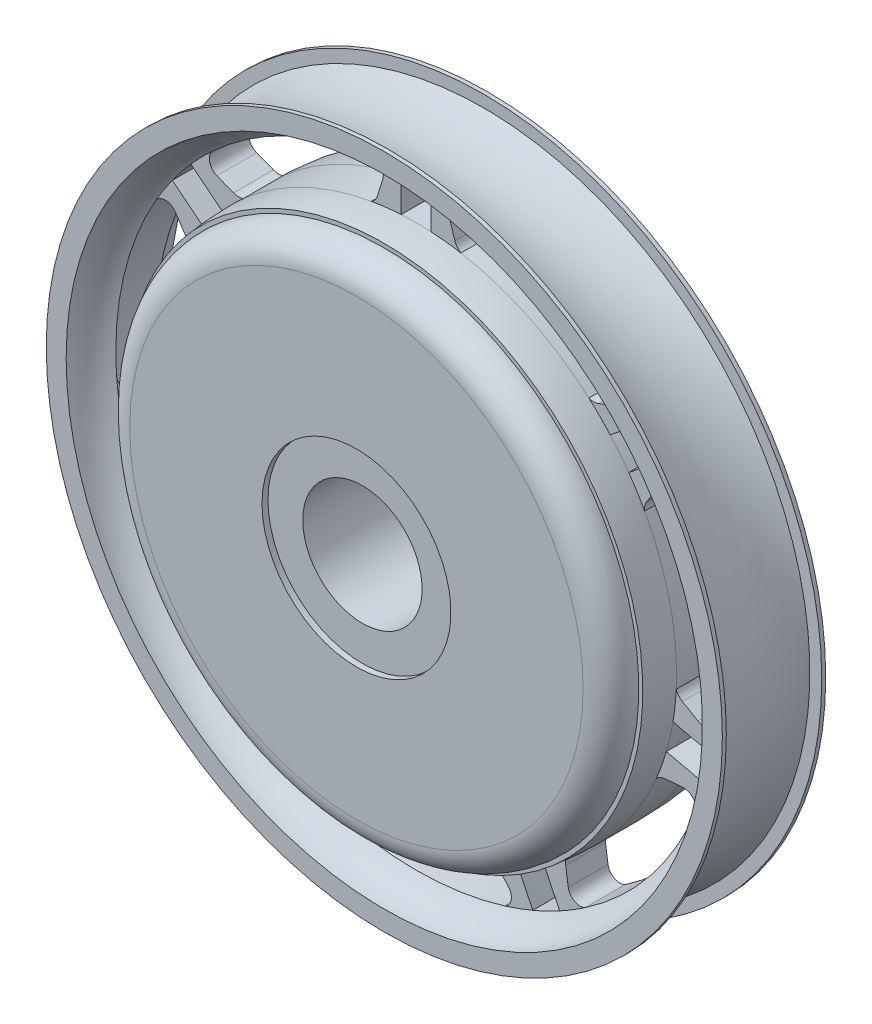
SolidWorks part; units mm, degrees
ref_plane "Спереди" through (0, 0, 0) normal (0, 0, 1) x (1, 0, 0)
ref_plane "Сверху" through (0, 0, 0) normal (0, 1, 0) x (1, 0, 0)
ref_plane "Справа" through (0, 0, 0) normal (1, 0, 0) x (0, 0, -1)
other "Configuration Table"
sketch "Sketch2" plane through (0, 0, 0) normal (0, 1, 0) x (1, 0, 0)
  line L0 (-47.5, -40) -> (-114, -40)
  line L1 (-114, 40) -> (-47.5, 40)
  line L2 (-30, 37) -> (-30, -37)
  line L3 (0, 135.3674) -> (0, -254.0086) construction
  line L4 (-170, 121.9099) -> (-170, -139.6695) construction
  line L5 (-130, 26) -> (-128, 26)
  line L7 (-170, -24) -> (-170, -26)
  line L9 (-221.397, 0) -> (79.0762, 0) construction
  line L10 (-47.5, 40) -> (-47.5, 37)
  line L11 (-47.5, 37) -> (-30, 37)
  line L12 (-47.5, -40) -> (-47.5, -37)
  line L13 (-47.5, -37) -> (-30, -37)
  line L14 (-131, 10) -> (-151, 10)
  line L15 (-160, 26) -> (-170, 26)
  line L16 (-170, 26) -> (-170, 24)
  line L17 (-130, -26) -> (-128, -26)
  line L18 (-131, -10) -> (-151, -10)
  line L19 (-160, -26) -> (-170, -26)
  line L20 (-170, 24) -> (-164, 24)
  line L22 (-164, -24) -> (-170, -24)
  arc A2 (-114, 40) -> (-128, 26) centre (-114, 26) ccw
  arc A4 (-114, -40) -> (-128, -26) centre (-114, -26) cw
  arc A5 (-131, 10) -> (-130, 26) centre (-2.5, 10) cw
  arc A6 (-151, 10) -> (-160, 26) centre (-140.0127, 26.7116) cw
  arc A8 (-131, -10) -> (-130, -26) centre (-2.5, -10) ccw
  arc A9 (-151, -10) -> (-160, -26) centre (-140.0127, -26.7116) ccw
  arc A10 (-164, -24) -> (-164, 24) centre (-218.9909, 0) ccw
  dimension "D1" = 140
  dimension "D7" = 3
  dimension "D13" = 60
  dimension "D15" = 20
  dimension "D2" = 80
  dimension "D3" = 60
  dimension "D4" = 2
  dimension "D5" = 6
  dimension "D6" = 95
  dimension "D8" = 98
  dimension "D9" = 3
  dimension "D10" = 2
  dimension "D11" = 20
  dimension "D12" = 10
  dimension "D14" = 20
  dimension "D16" = 52
revolve "Revolve1" add sketch "Sketch2" angle 360 about L3
sketch "Sketch3" plane through (0, 0, 10) normal (0, 0, 1) x (1, 0, 0)
  line L0 (0, 11.3109) -> (0, 206.172) construction
  line L1 (-7.5, 150.8136) -> (-7.5, 130.7851)
  line L2 (7.5, 150.8136) -> (7.5, 130.7851)
  line L3 (-16.7754, 141.5175) -> (-19.4706, 132.9305)
  line L4 (-22.5, 187.0326) -> (-22.5, 75.6795) construction
  line L5 (16.7754, 141.5175) -> (19.4706, 132.9305)
  line L6 (113.2347, 99.8945) -> (97.5758, 87.4069)
  line L7 (122.587, 88.167) -> (106.9281, 75.6795)
  line L8 (100.1835, 101.3502) -> (91.7896, 98.1035)
  line L9 (121.1021, 75.1192) -> (116.0689, 67.6581)
  line L10 (148.7013, -26.2472) -> (129.175, -21.7905)
  line L11 (145.3635, -40.8711) -> (125.8372, -36.4144)
  line L12 (141.7022, -15.1358) -> (133.9303, -10.5974)
  line L13 (134.2365, -47.8454) -> (125.2651, -48.5622)
  line L14 (72.1928, -132.6243) -> (63.5028, -114.5792)
  line L15 (58.6783, -139.1325) -> (49.9883, -121.0875)
  line L16 (76.5162, -120.2243) -> (75.2188, -111.3183)
  line L17 (46.2881, -134.7814) -> (40.134, -128.2142)
  line L18 (-58.6783, -139.1325) -> (-49.9883, -121.0875)
  line L19 (-72.1928, -132.6243) -> (-63.5028, -114.5792)
  line L20 (-46.2881, -134.7814) -> (-40.134, -128.2142)
  line L21 (-76.5162, -120.2243) -> (-75.2188, -111.3183)
  line L22 (-145.3635, -40.8711) -> (-125.8372, -36.4144)
  line L23 (-148.7013, -26.2472) -> (-129.175, -21.7905)
  line L24 (-134.2365, -47.8454) -> (-125.2651, -48.5622)
  line L25 (-141.7022, -15.1358) -> (-133.9303, -10.5974)
  line L26 (-122.587, 88.167) -> (-106.9281, 75.6795)
  line L27 (-113.2347, 99.8945) -> (-97.5758, 87.4069)
  line L28 (-121.1021, 75.1192) -> (-116.0689, 67.6581)
  line L29 (-100.1835, 101.3502) -> (-91.7896, 98.1035)
  circle A0 centre (0, 0) radius 151 construction
  circle A1 centre (0, 0) radius 131 construction
  arc A2 (-19.4706, 132.9305) -> (-22.5, 129.0533) centre (-26.1493, 135.0268) cw
  arc A3 (-16.7754, 141.5175) -> (-22.5, 149.3143) centre (-22.5, 143.3143) ccw
  arc A4 (19.4706, 132.9305) -> (22.5, 129.0533) centre (26.1493, 135.0268) ccw
  circle A5 centre (0, 0) radius 151
  circle A6 centre (0, 0) radius 151
  arc A7 (16.7754, 141.5175) -> (22.5, 149.3143) centre (22.5, 143.3143) cw
  arc A8 (91.7896, 98.1035) -> (86.8694, 98.0546) centre (89.2644, 104.6322) cw
  arc A9 (100.1835, 101.3502) -> (102.7101, 110.6871) centre (98.0191, 106.9462) ccw
  arc A10 (116.0689, 67.6581) -> (114.9264, 62.8722) centre (121.872, 63.7435) ccw
  arc A11 (121.1021, 75.1192) -> (130.7671, 75.5047) centre (126.0761, 71.7638) cw
  arc A12 (133.9303, -10.5974) -> (130.8244, -6.7812) centre (137.4601, -4.5526) cw
  arc A13 (141.7022, -15.1358) -> (150.5774, -11.2897) centre (144.7278, -9.9545) ccw
  arc A14 (125.2651, -48.5622) -> (120.8109, -50.6529) centre (125.8226, -55.54) ccw
  arc A15 (134.2365, -47.8454) -> (140.5639, -55.1614) centre (134.7144, -53.8263) cw
  arc A16 (75.2188, -111.3183) -> (76.2659, -106.5106) centre (82.1456, -110.3092) cw
  arc A17 (76.5162, -120.2243) -> (85.0568, -124.7651) centre (82.4535, -119.3593) ccw
  arc A18 (40.134, -128.2142) -> (35.7223, -126.0354) centre (35.0262, -133.0007) ccw
  arc A19 (46.2881, -134.7814) -> (44.5132, -144.2899) centre (41.9099, -138.8841) cw
  arc A20 (-40.134, -128.2142) -> (-35.7223, -126.0354) centre (-35.0262, -133.0007) cw
  arc A21 (-46.2881, -134.7814) -> (-44.5132, -144.2899) centre (-41.9099, -138.8841) ccw
  arc A22 (-75.2188, -111.3183) -> (-76.2659, -106.5106) centre (-82.1456, -110.3092) ccw
  arc A23 (-76.5162, -120.2243) -> (-85.0568, -124.7651) centre (-82.4535, -119.3593) cw
  arc A24 (-125.2651, -48.5622) -> (-120.8109, -50.6529) centre (-125.8226, -55.54) cw
  arc A25 (-134.2365, -47.8454) -> (-140.5639, -55.1614) centre (-134.7144, -53.8263) ccw
  arc A26 (-133.9303, -10.5974) -> (-130.8244, -6.7812) centre (-137.4601, -4.5526) ccw
  arc A27 (-141.7022, -15.1358) -> (-150.5774, -11.2897) centre (-144.7278, -9.9545) cw
  arc A28 (-116.0689, 67.6581) -> (-114.9264, 62.8722) centre (-121.872, 63.7435) cw
  arc A29 (-121.1021, 75.1192) -> (-130.7671, 75.5047) centre (-126.0761, 71.7638) ccw
  arc A30 (-91.7896, 98.1035) -> (-86.8694, 98.0546) centre (-89.2644, 104.6322) ccw
  arc A31 (-100.1835, 101.3502) -> (-102.7101, 110.6871) centre (-98.0191, 106.9462) cw
  point P127 (0, 0)
  circle M8 centre (0, 0) radius 131
  circle M9 centre (0, 0) radius 151
  dimension "D4" = 7
  dimension "D5" = 6
  dimension "D1" = 15
  dimension "D3" = 15
  dimension "D6" = 9
  dimension "D2" = 0
  dimension "D7" = 7
extrude "Cut-Extrude1" cut sketch "Sketch3" against normal through all both and the other way through all contours A31 L29 A30 A2 L3 A3 M8 M9 | L27 L26 M9 M8 | L28 A29 A6 A27 L25 A26 A28 M8 | L23 L22 M9 M8 | L24 A25 A6 A23 L21 A22 A24 M8 | L19 L18 M9 M8 | L20 A21 A6 A19 L17 A18 A20 M8 | L16 A17 A6 A15 L13 A14 A16 M8 | L11 L10 M9 M8 | L12 A13 A6 A11 L9 A10 A12 M8 | L7 L6 M9 M8 | L8 A9 A6 A7 L5 A4 A8 M8 | L2 L1 M9 M8 | L15 L14 M9 M8
equation "\"D3@Sketch3\"=\"D1@Sketch3\""
